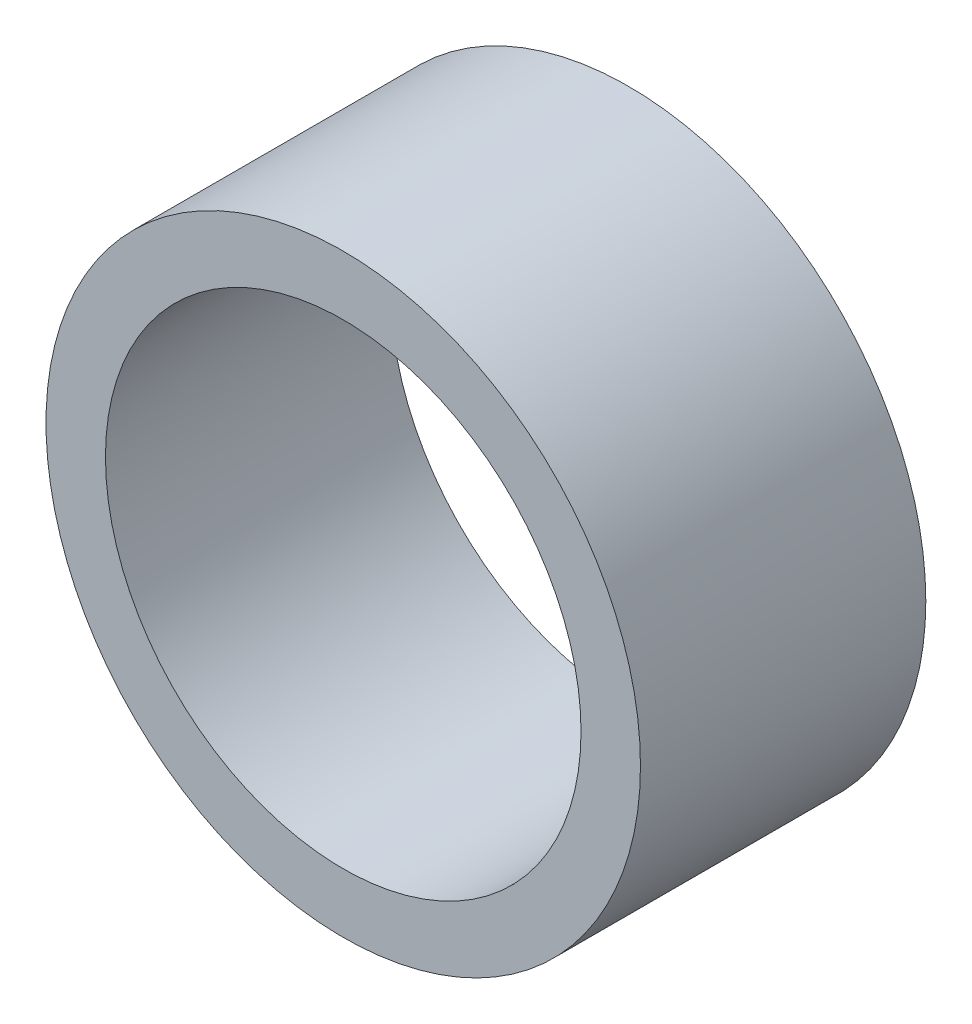
SolidWorks part; units mm, degrees
material "Chêne"
ref_plane "Plan de face" through (0, 0, 0) normal (0, 0, 1) x (1, 0, 0)
ref_plane "Plan de dessus" through (0, 0, 0) normal (0, 1, 0) x (1, 0, 0)
ref_plane "Plan de droite" through (0, 0, 0) normal (1, 0, 0) x (0, 0, -1)
sketch "Esquisse1" plane through (0, 0, 0) normal (0, 0, 1) x (1, 0, 0)
  circle A0 centre (0, 0) radius 12.5
  circle A4 centre (0, 0) radius 10
  point P116 (0, 0)
  point P374 (0, 0)
extrude "Boss.-Extru.1" add sketch "Esquisse1" along normal blind 12
